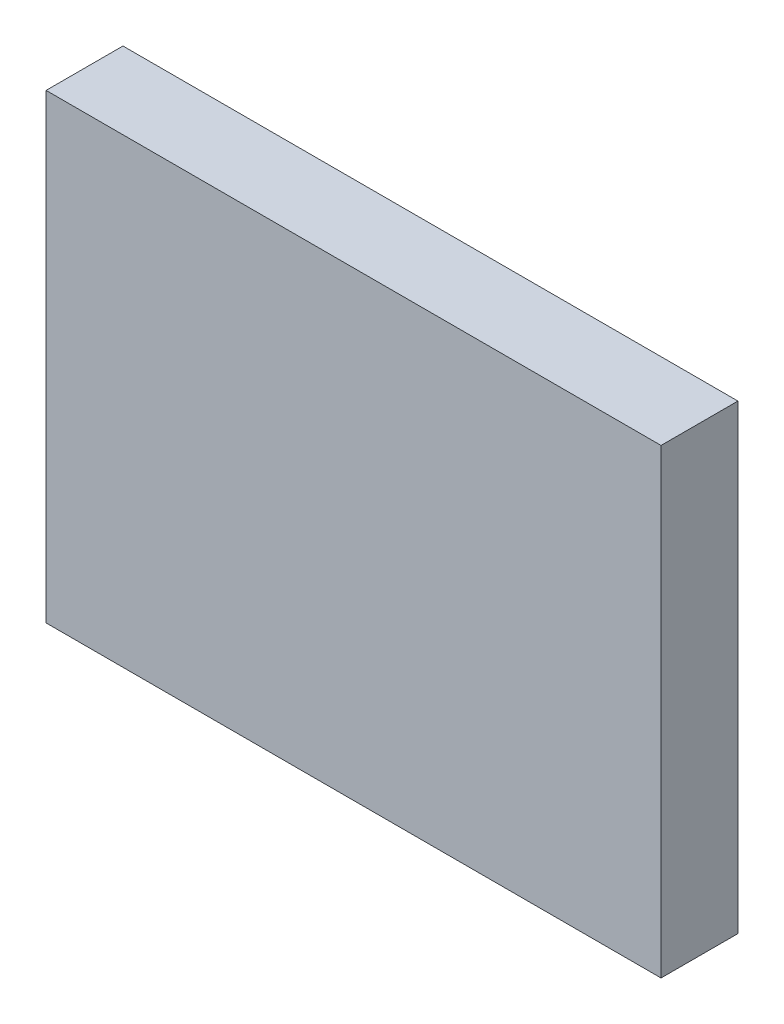
SolidWorks part; units mm, degrees
ref_plane "Front Plane" through (0, 0, 0) normal (0, 0, 1) x (1, 0, 0)
ref_plane "Top Plane" through (0, 0, 0) normal (0, 1, 0) x (1, 0, 0)
ref_plane "Right Plane" through (0, 0, 0) normal (1, 0, 0) x (0, 0, -1)
sketch "Sketch1" plane through (0, 0, 0) normal (0, 0, 1) x (1, 0, 0)
  line L1 (0, 0) -> (101.6, 0)
  line L2 (0, 0) -> (0, 76.2)
  line L3 (0, 76.2) -> (101.6, 76.2)
  line L4 (101.6, 0) -> (101.6, 76.2)
extrude "Boss-Extrude1" add sketch "Sketch1" along normal blind 12.7
sketch "Sketch2" plane through (0, 0, 0) normal (0, 1, 0) x (1, 0, 0)
  line L1 (0, 0) -> (25.4, 0)
  line L2 (0, 0) -> (0, 25.4)
  line L3 (0, 25.4) -> (25.4, 25.4)
  line L4 (25.4, 0) -> (25.4, 25.4)
